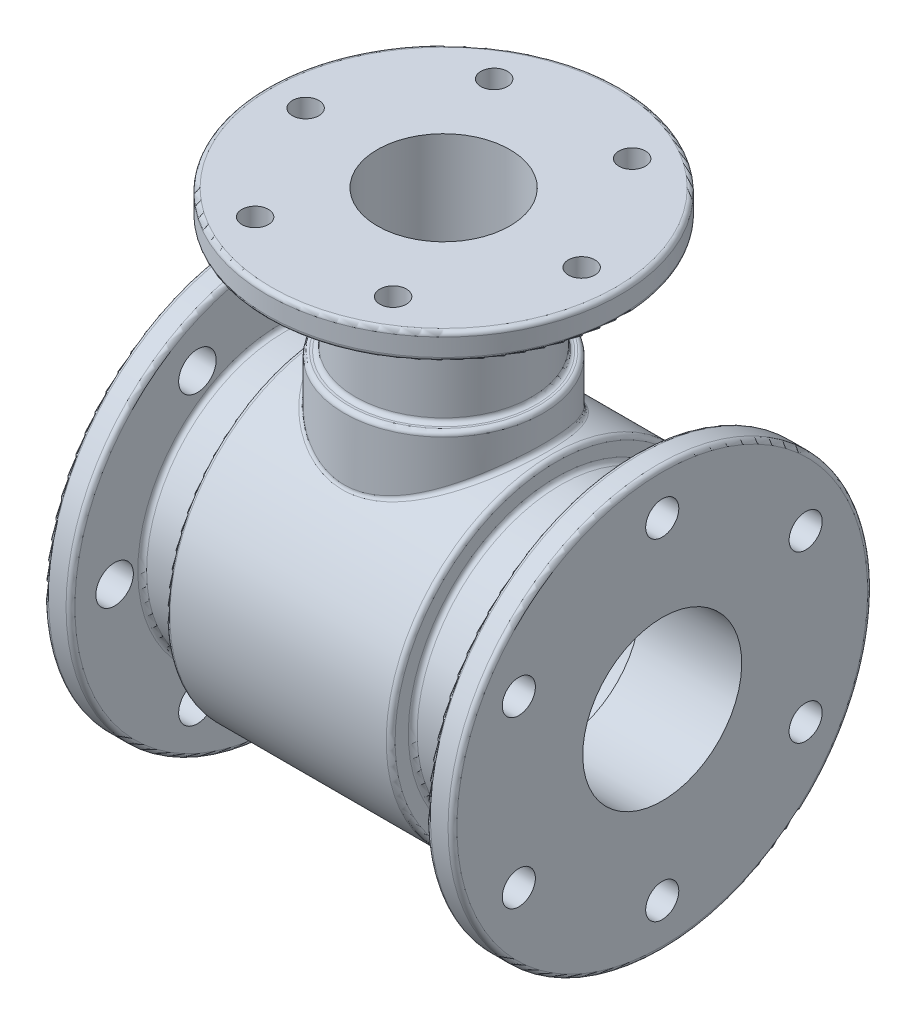
SolidWorks part; units mm, degrees
ref_plane "Front Plane" through (0, 0, 0) normal (0, 0, 1) x (1, 0, 0)
ref_plane "Top Plane" through (0, 0, 0) normal (0, 1, 0) x (1, 0, 0)
ref_plane "Right Plane" through (0, 0, 0) normal (1, 0, 0) x (0, 0, -1)
sketch "Sketch1" plane through (0, 0, 0) normal (0, 0, 1) x (1, 0, 0)
  line L0 (0, 0) -> (-58317.2914, 0) construction
  line L1 (0, -31.6379) -> (0, -58348.9293) construction
  line L2 (99, -36) -> (99, -95)
  line L3 (99, -95) -> (87, -95)
  line L4 (87, -95) -> (87, -50)
  line L5 (87, -50) -> (73, -50)
  line L6 (73, -50) -> (73, -65)
  line L7 (73, -65) -> (51, -65)
  line L8 (51, -65) -> (51, -75)
  line L9 (51, -75) -> (-51, -75)
  line L10 (-51, -75) -> (-51, -62.5)
  line L11 (-51, -62.5) -> (-74, -62.5)
  line L12 (-74, -62.5) -> (-74, -95)
  line L13 (-74, -95) -> (-86, -95)
  line L14 (-86, -95) -> (-86, -52.5)
  line L15 (-81, -47.5) -> (-36, -47.5)
  line L16 (-36, -47.5) -> (-36, -50.5)
  line L17 (-34, -52.5) -> (34, -52.5)
  line L18 (36, -50.5) -> (36, -43.5)
  line L19 (36, -43.5) -> (51, -43.5)
  line L20 (53, -41.5) -> (53, -36)
  line L21 (53, -36) -> (99, -36)
  line L22 (-86, -52.5) -> (-81, -52.5)
  line L23 (-81, -52.5) -> (-81, -47.5)
  line L24 (51, -43.5) -> (53, -41.5)
  arc A0 (34, -52.5) -> (36, -50.5) centre (34, -50.5) ccw
  arc A1 (-34, -52.5) -> (-36, -50.5) centre (-34, -50.5) cw
  point P17 (53, -43.5)
  point P31 (-36, -52.5)
  point P32 (0, 0)
  dimension "D19" = 2
  dimension "D1" = 72
  dimension "D2" = 87
  dimension "D3" = 100
  dimension "D4" = 130
  dimension "D5" = 12
  dimension "D6" = 185
  dimension "D7" = 26
  dimension "D8" = 46
  dimension "D9" = 63
  dimension "D10" = 190
  dimension "D11" = 135
  dimension "D12" = 150
  dimension "D13" = 105
  dimension "D14" = 150
  dimension "D15" = 95
  dimension "D16" = 105
  dimension "D17" = 125
  dimension "D18" = 5
  dimension "D20" = 2
  dimension "D21" = 45
revolve "Revolve1" add sketch "Sketch1" angle 360 about L0
sketch "Sketch2" plane through (0, 0, 0) normal (0, 0, 1) x (1, 0, 0)
  line L0 (0, 0) -> (-50000, 0) construction
  line L1 (0, 0) -> (0, -50000) construction
  line L2 (0, 155) -> (80, 155)
  line L3 (80, 155) -> (80, 143)
  line L4 (80, 143) -> (40, 143)
  line L5 (40, 143) -> (40, 91)
  line L6 (40, 91) -> (45, 91)
  line L7 (45, 91) -> (45, 75)
  line L8 (45, 75) -> (0, 75)
  line L11 (0, 75) -> (0, 155)
  dimension "D1" = 12
  dimension "D2" = 64
  dimension "D3" = 80
  dimension "D5" = 90
  dimension "D6" = 80
  dimension "D7" = 160
  dimension "D8" = 155
revolve "Revolve2" add sketch "Sketch2" angle 360 about L1
sketch "Sketch3" plane through (0, 75, 0) normal (0, -1, 0) x (1, 0, 0)
  circle A1 centre (0, 0) radius 45
  circle A2 centre (0, 0) radius 45
  dimension "D1" = 0
extrude "Boss-Extrude1" add sketch "Sketch3" along normal up to surface up to face at (51, 75, 0)
hole_wizard "Ø6.0mm Dowel Hole1" positions "Sketch4" profile "Sketch6" hole size "Ø6.0" standard "ANSI Metric"
sketch "Sketch4" plane through (0, 155, 0) normal (0, 1, 0) x (1, 0, 0)
  point P0 (0, 0)
sketch "Sketch6" plane through (0, 155, 0) normal (1, 0, 0) x (0, 0, 1)
  line L0 (0, 0) -> (0, 102.5)
  line L1 (0, 102.5) -> (30, 102.5)
  line L2 (30, 102.5) -> (30, 0)
  line L5 (30, 0) -> (0, 0)
  line L11 (0, -6.35) -> (0, 107.95) construction
  dimension "Thru Hole Dia." = 60
  dimension "Thru Hole Depth" = 102.5
hole_wizard "Ø6.0mm Dowel Hole2" positions "Sketch7" profile "Sketch8" hole size "Ø6.0" standard "ANSI Metric"
sketch "Sketch7" plane through (99, 0, 0) normal (1, 0, 0) x (0, 0, -1)
  point P0 (0, 75)
  dimension "D1" = 75
sketch "Sketch8" plane through (99, 75, 0) normal (0, 1, 0) x (0, 0, -1)
  line L0 (0, 0) -> (0, 12)
  line L1 (0, 12) -> (7.5, 12)
  line L2 (7.5, 12) -> (7.5, 0)
  line L5 (7.5, 0) -> (0, 0)
  line L11 (0, -6.35) -> (0, 107.95) construction
  dimension "Thru Hole Dia." = 15
  dimension "Thru Hole Depth" = 12
pattern_circular "CirPattern1" count 6 over 360 about axis through (0, 0, 0) along (1, 0, 0) of "Ø6.0mm Dowel Hole2"
hole_wizard "Ø6.0mm Dowel Hole3" positions "Sketch9" profile "Sketch10" hole size "Ø6.0" standard "ANSI Metric"
sketch "Sketch9" plane through (-86, 0, 0) normal (-1, 0, 0) x (0, 0, 1)
  point P0 (75, 0)
  dimension "D1" = 75
sketch "Sketch10" plane through (-86, 0, 75) normal (0, 1, 0) x (0, 0, 1)
  line L0 (0, 0) -> (0, 12)
  line L1 (0, 12) -> (8.5, 12)
  line L2 (8.5, 12) -> (8.5, 0)
  line L5 (8.5, 0) -> (0, 0)
  line L11 (0, -6.35) -> (0, 107.95) construction
  dimension "Thru Hole Dia." = 17
  dimension "Thru Hole Depth" = 12
pattern_circular "CirPattern2" count 6 over 360 about axis through (0, 0, 0) along (1, 0, 0) of "Ø6.0mm Dowel Hole3"
hole_wizard "Ø6.0mm Dowel Hole4" positions "Sketch11" profile "Sketch12" hole size "Ø6.0" standard "ANSI Metric"
sketch "Sketch11" plane through (0, 155, 0) normal (0, 1, 0) x (1, 0, 0)
  point P0 (62.5, 0)
  dimension "D1" = 62.5
sketch "Sketch12" plane through (62.5, 155, 0) normal (1, 0, 0) x (0, 0, 1)
  line L0 (0, 0) -> (0, 12)
  line L1 (0, 12) -> (6, 12)
  line L2 (6, 12) -> (6, 0)
  line L5 (6, 0) -> (0, 0)
  line L11 (0, -6.35) -> (0, 107.95) construction
  dimension "Thru Hole Dia." = 12
  dimension "Thru Hole Depth" = 12
pattern_circular "CirPattern3" count 6 over 360 about axis through (0, 0, 0) along (0, 1, 0) of "Ø6.0mm Dowel Hole4"
fillet "Fillet1" radius 2 18 edges at (-86, 95, 0) (-74, 95, 0) (-74, 62.5, 0) (-51, 62.5, 0) (-51, 75, 0) (51, 75, 0) (51, 65, 0) (73, 65, 0) (73, 50, 0) (87, 50, 0) (87, 95, 0) (99, 95, 0) (-0.0973, 60.0001, -44.9999) (0, 155, 80) (0, 143, 80) (0, 143, 40) (0, 91, 40) (0, 91, 45)
